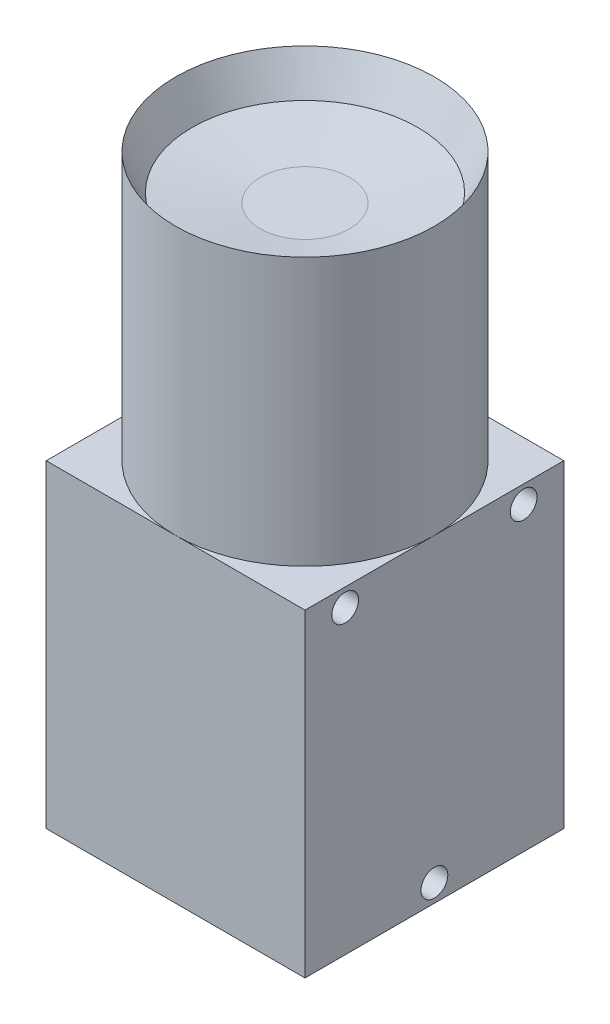
SolidWorks part; units mm, degrees
ref_plane "前视基准面" through (0, 0, 0) normal (0, 0, 1) x (1, 0, 0)
ref_plane "上视基准面" through (0, 0, 0) normal (0, 1, 0) x (1, 0, 0)
ref_plane "右视基准面" through (0, 0, 0) normal (1, 0, 0) x (0, 0, -1)
sketch "草图1" plane through (0, 0, 0) normal (0, 0, 1) x (1, 0, 0)
  line L0 (0, 0) -> (-14.5, 0)
  line L1 (-14.5, 0) -> (-14.5, 30)
  line L5 (0, 25) -> (0, 0)
  line L7 (-5, 25) -> (0, 25)
  line L8 (-14.5, 30) -> (-12.6469, 26.018)
  line L9 (-12.6469, 26.018) -> (-5, 25)
  dimension "D4" = 30
  dimension "D5" = 14.5
  dimension "D6" = 25
  dimension "D7" = 5
revolve "旋转1" add sketch "草图1" angle 360 about L5
sketch "草图2" plane through (0, 0, 0) normal (0, -1, 0) x (1, 0, 0)
  line L1 (-14.5, 14.5) -> (14.5, 14.5)
  line L2 (-14.5, 14.5) -> (-14.5, -14.5)
  line L3 (-14.5, -14.5) -> (14.5, -14.5)
  line L4 (14.5, 14.5) -> (14.5, -14.5)
  line L5 (-14.5, 14.5) -> (14.5, -14.5) construction
  line L6 (-14.5, -14.5) -> (14.5, 14.5) construction
  circle A0 centre (0, 0) radius 14.5 construction
  point P0 (0, 0)
extrude "凸台-拉伸1" add sketch "草图2" along normal blind 35.7
sketch "草图3" plane through (0, 0, -14.5) normal (0, 0, -1) x (-1, 0, 0)
  line L0 (0, 0) -> (0, -35.7) construction
  line L1 (14.5, -35.7) -> (-14.5, -35.7) construction
  line L2 (0, 0) -> (-14.5, 0) construction
  circle A0 centre (-10, -2) radius 1.5
  circle A1 centre (-10, -33.7) radius 1.5
  circle A2 centre (10, -33.7) radius 1.5
  circle A3 centre (10, -2) radius 1.5
  dimension "D2" = 3
  dimension "D1" = 10
  dimension "D3" = 2
  dimension "D4" = 2
extrude "切除-拉伸1" cut sketch "草图3" against normal blind 4
sketch "草图4" plane through (14.5, 0, 0) normal (1, 0, 0) x (0, 0, -1)
  line L0 (0, 0) -> (0, -35.7) construction
  line L1 (14.5, -35.7) -> (-14.5, -35.7) construction
  line L2 (0, 0) -> (-14.5, 0) construction
  circle A0 centre (-10, -2) radius 1.5
  circle A1 centre (0, -33.7) radius 1.5
  circle A2 centre (10, -2) radius 1.5
  dimension "D1" = 3
  dimension "D2" = 2
  dimension "D3" = 10
  dimension "D4" = 2
extrude "切除-拉伸2" cut sketch "草图4" against normal up to next
